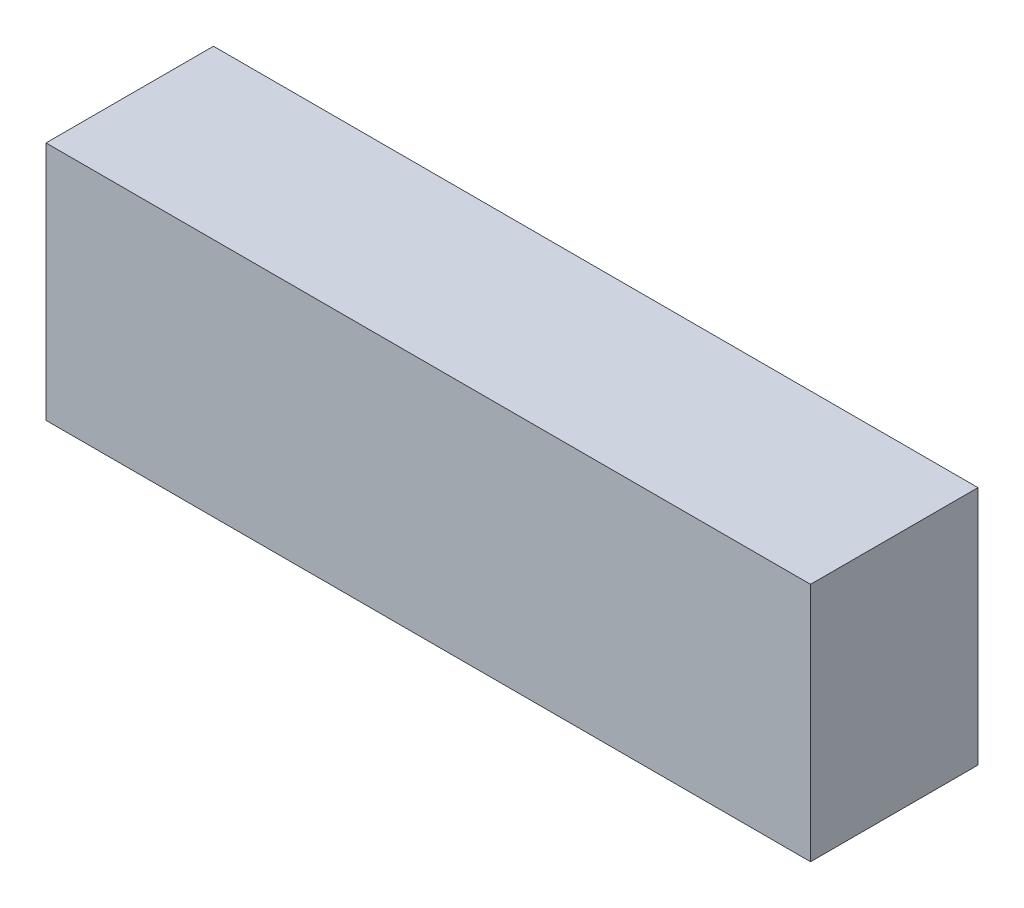
SolidWorks part; units mm, degrees
ref_plane "前视基准面" through (0, 0, 0) normal (0, 0, 1) x (1, 0, 0)
ref_plane "上视基准面" through (0, 0, 0) normal (0, 1, 0) x (1, 0, 0)
ref_plane "右视基准面" through (0, 0, 0) normal (1, 0, 0) x (0, 0, -1)
sketch "草图1" plane through (0, 0, 0) normal (0, 0, 1) x (1, 0, 0)
  line L1 (-52.5, 16.5) -> (52.5, 16.5)
  line L2 (-52.5, 16.5) -> (-52.5, -16.5)
  line L3 (-52.5, -16.5) -> (52.5, -16.5)
  line L4 (52.5, 16.5) -> (52.5, -16.5)
  line L5 (-52.5, 16.5) -> (52.5, -16.5) construction
  line L6 (-52.5, -16.5) -> (52.5, 16.5) construction
  point P0 (0, 0)
  dimension "D1" = 105
  dimension "D2" = 33
extrude "凸台-拉伸1" add sketch "草图1" along normal blind 23
